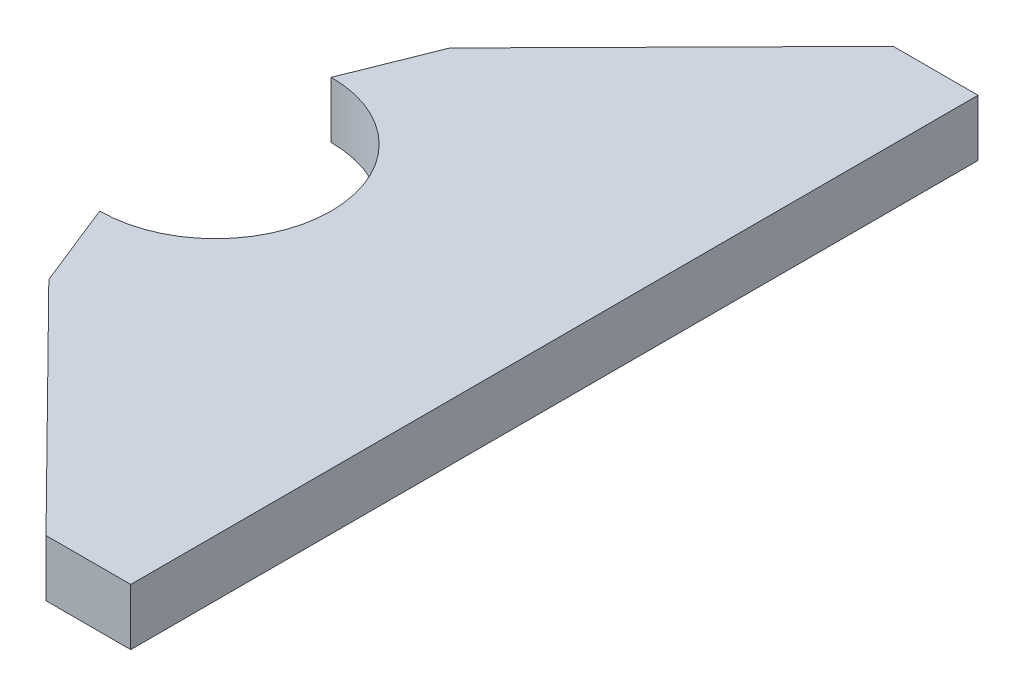
SolidWorks part; units mm, degrees
ref_plane "Ön Düzlem" through (0, 0, 0) normal (0, 0, 1) x (1, 0, 0)
ref_plane "Üst Düzlem" through (0, 0, 0) normal (0, 1, 0) x (1, 0, 0)
ref_plane "Sağ Düzlem" through (0, 0, 0) normal (1, 0, 0) x (0, 0, -1)
sketch "Sketch1" plane through (0, 0, 0) normal (0, 1, 0) x (1, 0, 0)
  line L0 (-3.4463, -20.5) -> (2.5537, -35.5)
  line L1 (41.5537, -75) -> (56.5537, -75)
  line L2 (2.5537, -35.5) -> (41.5537, -75)
  line L3 (41.5537, 75) -> (56.5537, 75)
  line L4 (56.5537, -75) -> (56.5537, 75)
  line L5 (137.7611, 0) -> (-63.7923, 0) construction
  line L6 (-3.4463, 20.5) -> (2.5537, 35.5)
  line L7 (2.5537, 35.5) -> (41.5537, 75)
  arc A0 (-3.4463, -20.5) -> (-3.4463, 20.5) centre (-3.4463, 0) ccw
  point P0 (0, 0)
  dimension "D2" = 20.5
  dimension "D1" = 150
  dimension "D3" = 15
  dimension "D4" = 75
  dimension "D5" = 15
  dimension "D6" = 6
  dimension "D7" = 15
  dimension "D8" = 6
  dimension "D9" = 60
extrude "Boss-Extrude1" add sketch "Sketch1" along normal blind 10
sketch "Sketch2" plane through (0, 0, 0) normal (0, -1, 0) x (1, 0, 0)
  line L0 (56.5537, 2) -> (56.5537, -2) construction
  line L1 (56.5537, 75) -> (56.5537, -75) construction
  circle A0 centre (58.0537, 0) radius 2.5
  point P4 (56.5537, 0)
  dimension "D2" = 5
  dimension "D1" = 4
